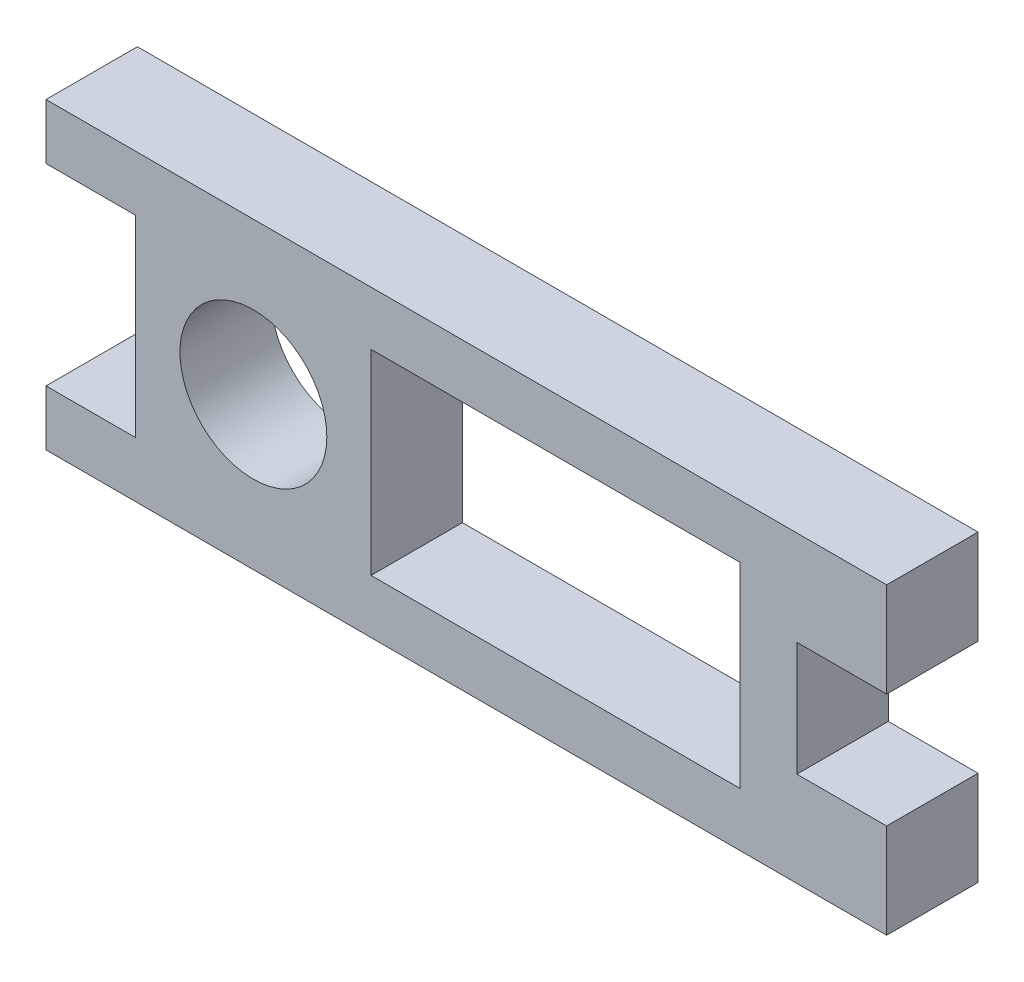
SolidWorks part; units mm, degrees
material "Acrylic (Medium-high impact)"
ref_plane "Front Plane" through (0, 0, 0) normal (0, 0, 1) x (1, 0, 0)
ref_plane "Top Plane" through (0, 0, 0) normal (0, 1, 0) x (1, 0, 0)
ref_plane "Right Plane" through (0, 0, 0) normal (1, 0, 0) x (0, 0, -1)
sketch "Sketch1" plane through (0, 0, 0) normal (0, 0, 1) x (1, 0, 0)
  line L0 (-297.7097, 397.7995) -> (49702.2903, 397.7995) construction
  line L1 (704.2544, 403.6995) -> (704.2544, 391.8995)
  line L2 (704.2544, 403.6995) -> (698.7544, 403.6995)
  line L3 (698.7544, 403.6995) -> (698.7544, 407.0995)
  line L4 (698.7544, 407.0995) -> (750.2744, 407.0995)
  line L5 (750.2744, 407.0995) -> (750.2744, 401.2995)
  line L6 (750.2744, 401.2995) -> (744.7744, 401.2995)
  line L7 (744.7744, 401.2995) -> (744.7744, 394.2995)
  line L8 (744.7744, 394.2995) -> (750.2744, 394.2995)
  line L9 (750.2744, 394.2995) -> (750.2744, 388.4995)
  line L10 (750.2744, 388.4995) -> (698.7544, 388.4995)
  line L11 (698.7544, 388.4995) -> (698.7544, 391.8995)
  line L12 (698.7544, 391.8995) -> (704.2544, 391.8995)
  line L13 (724.5144, 425.1376) -> (724.5144, 373.1851) construction
  line L14 (718.6744, 391.7995) -> (741.2744, 391.7995)
  line L15 (718.6744, 391.7995) -> (718.6744, 403.7995)
  line L16 (718.6744, 403.7995) -> (741.2744, 403.7995)
  line L17 (741.2744, 391.7995) -> (741.2744, 403.7995)
  line L18 (718.6744, 397.7995) -> (704.2544, 397.7995) construction
  line L19 (718.6744, 397.7995) -> (704.2544, 397.7995) construction
  line L20 (718.6744, 397.7995) -> (704.2544, 397.7995) construction
  line L21 (704.2544, 397.7995) -> (711.4644, 397.7995) construction
  line L22 (711.4644, 397.7995) -> (711.4644, 412.076) construction
  circle A0 centre (711.4644, 397.7995) radius 4.5
  point P0 (704.2544, 397.7995)
  point P23 (724.5144, 397.7995)
  dimension "D10" = 9
  dimension "D2" = 3.4
  dimension "D4" = 5.5
  dimension "D5" = 5.5
  dimension "D6" = 5.8
  dimension "D7" = 7
  dimension "D3" = 22.6
  dimension "D8" = 12
  dimension "D9" = 5.84
  dimension "D12" = 14.42
  dimension "D11" = 11.8
  dimension "Hip_top_half_width" = 20.26
extrude "Boss-Extrude1" add sketch "Sketch1" along normal blind 5.6
equation "\"D3@Sketch1\"=\"Servo_length@Servo-1.Part\""
equation "\"D8@Sketch1\"=\"Servo_width@Servo-1.Part\""
equation "\"D9@Sketch1\"=\"Servo_boss_radius@Servo-1.Part\""
